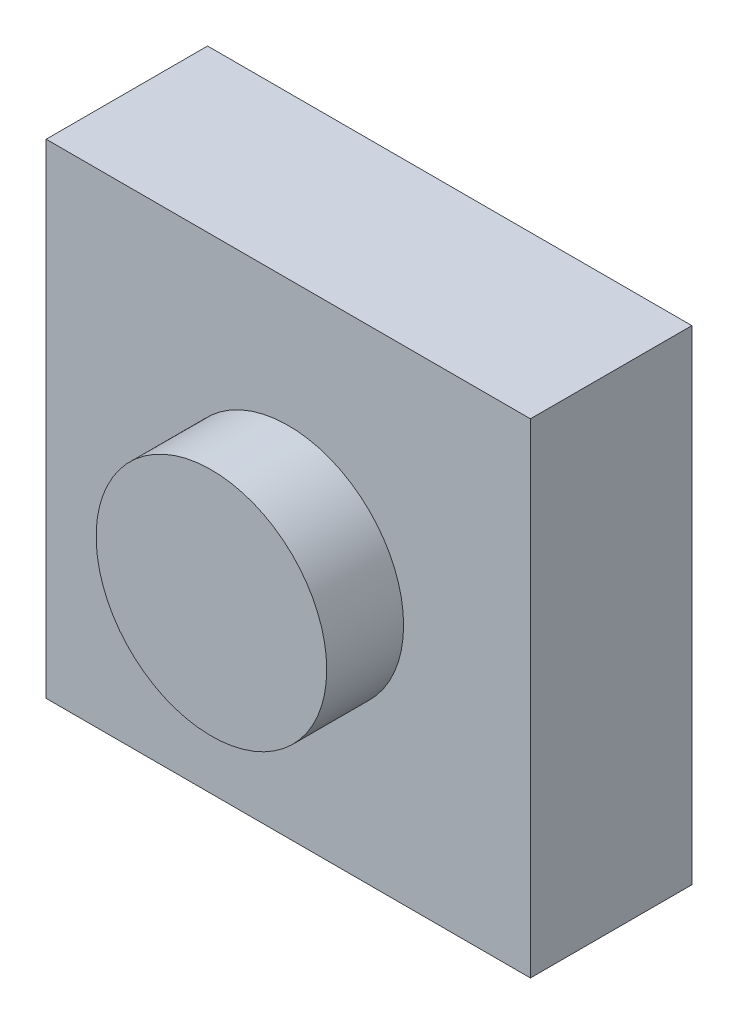
SolidWorks part; units mm, degrees
ref_plane "Alzado" through (0, 0, 0) normal (0, 0, 1) x (1, 0, 0)
ref_plane "Planta" through (0, 0, 0) normal (0, 1, 0) x (1, 0, 0)
ref_plane "Vista lateral" through (0, 0, 0) normal (1, 0, 0) x (0, 0, -1)
sketch "Croquis1" plane through (0, 0, 0) normal (0, 0, 1) x (1, 0, 0)
  line L1 (3.15, -3.15) -> (-3.15, -3.15)
  line L2 (3.15, -3.15) -> (3.15, 3.15)
  line L3 (3.15, 3.15) -> (-3.15, 3.15)
  line L4 (-3.15, -3.15) -> (-3.15, 3.15)
  line L5 (3.15, -3.15) -> (-3.15, 3.15) construction
  line L6 (3.15, 3.15) -> (-3.15, -3.15) construction
  point P0 (0, 0)
  dimension "D1" = 6.3
extrude "Saliente-Extruir1" add sketch "Croquis1" along normal blind 2.1
sketch "Croquis2" plane through (0, 0, 2.1) normal (0, 0, 1) x (1, 0, 0)
  circle A0 centre (0, 0) radius 1.5
  dimension "D1" = 3
extrude "Saliente-Extruir2" add sketch "Croquis2" along normal blind 1
